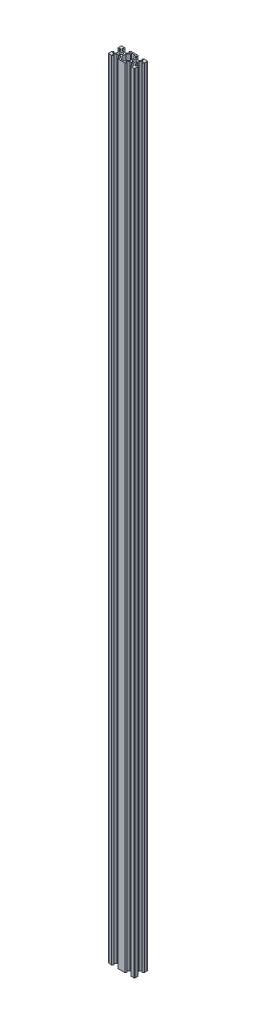
SolidWorks part; units mm, degrees
material "6063-T5"
material "6063-T5"
ref_plane "Plano frontal" through (0, 0, 0) normal (0, 0, 1) x (1, 0, 0)
ref_plane "Plano superior" through (0, 0, 0) normal (0, 1, 0) x (1, 0, 0)
ref_plane "Plano direito" through (0, 0, 0) normal (1, 0, 0) x (0, 0, -1)
sketch "Esboço1" plane through (0, 0, 0) normal (0, 0, 1) x (1, 0, 0)
  line L0 (0, 0) -> (0, 1200)
  dimension "D1" = 1200
other "Retangular PF20-12 - PERFIL 2040 V-SLOT(1)"
ref_plane "Plano1" through (0, 0, 0) normal (0, 1, 0) x (-1, 0, 0)
sketch "Sketch13" plane through (0, 0, 0) normal (0, 1, 0) x (-1, 0, 0)
  line L0 (-14.8, 10) -> (-13, 8.2)
  line L1 (-13, 8.2) -> (-15.5, 8.2)
  line L2 (-15.5, 8.2) -> (-15.5, 6.5607)
  line L3 (-15.5, 6.5607) -> (-12.9393, 4)
  line L4 (-12.9393, 4) -> (-10.3, 4)
  line L5 (-4.5, 6.5607) -> (-7.0607, 4)
  line L6 (-4.5, 8.2) -> (-4.5, 6.5607)
  line L7 (-7, 8.2) -> (-4.5, 8.2)
  line L8 (-5.2, 10) -> (-7, 8.2)
  line L9 (-10.3, 4) -> (-10, 3.7)
  line L10 (-9.7, 4) -> (-10, 3.7)
  line L11 (-9.7, 4) -> (-7.0607, 4)
  line L12 (-2.7, 8.2) -> (-2.7, 6.2393)
  line L13 (-2.7, 6.2393) -> (-6, 2.9393)
  line L14 (-2.7, 8.2) -> (2.7, 8.2)
  line L15 (2.7, 6.2393) -> (6, 2.9393)
  line L16 (2.7, 8.2) -> (2.7, 6.2393)
  line L17 (-5.2, -10) -> (5.2, -10)
  line L18 (-5.2, -10) -> (-7, -8.2)
  line L19 (-7, -8.2) -> (-4.5, -8.2)
  line L20 (-4.5, -8.2) -> (-4.5, -6.5607)
  line L21 (-4.5, -6.5607) -> (-7.0607, -4)
  line L22 (-7.0607, -4) -> (-9.7, -4)
  line L23 (-9.7, -4) -> (-10, -3.7)
  line L24 (-10.3, -4) -> (-10, -3.7)
  line L25 (-10.3, -4) -> (-12.9393, -4)
  line L26 (-15.5, -6.5607) -> (-12.9393, -4)
  line L27 (-15.5, -8.2) -> (-15.5, -6.5607)
  line L28 (-13, -8.2) -> (-15.5, -8.2)
  line L29 (-14.8, -10) -> (-13, -8.2)
  line L30 (-20, -4.8) -> (-20, -9)
  line L31 (-20, -4.8) -> (-18.2, -3)
  line L32 (-18.2, -3) -> (-18.2, -5.5)
  line L33 (-18.2, -5.5) -> (-16.5607, -5.5)
  line L34 (-16.5607, -5.5) -> (-14, -2.9393)
  line L35 (-14, -2.9393) -> (-14, -0.3)
  line L36 (-14, -0.3) -> (-13.7, 0)
  line L37 (-14, 0.3) -> (-13.7, 0)
  line L38 (-14, 0.3) -> (-14, 2.9393)
  line L39 (-16.5607, 5.5) -> (-14, 2.9393)
  line L40 (-18.2, 5.5) -> (-16.5607, 5.5)
  line L41 (-18.2, 3) -> (-18.2, 5.5)
  line L42 (-20, 4.8) -> (-18.2, 3)
  line L43 (-14.8, 10) -> (-19, 10)
  line L56 (5.2, 10) -> (-5.2, 10)
  line L57 (5.2, 10) -> (7, 8.2)
  line L58 (7, 8.2) -> (4.5, 8.2)
  line L59 (4.5, 8.2) -> (4.5, 6.5607)
  line L60 (4.5, 6.5607) -> (7.0607, 4)
  line L61 (9.7, 4) -> (7.0607, 4)
  line L62 (9.7, 4) -> (10, 3.7)
  line L63 (10.3, 4) -> (10, 3.7)
  line L64 (12.9393, 4) -> (10.3, 4)
  line L65 (15.5, 6.5607) -> (12.9393, 4)
  line L66 (15.5, 8.2) -> (15.5, 6.5607)
  line L67 (13, 8.2) -> (15.5, 8.2)
  line L68 (14.8, 10) -> (13, 8.2)
  line L69 (20, 4.8) -> (18.2, 3)
  line L70 (18.2, 3) -> (18.2, 5.5)
  line L71 (18.2, 5.5) -> (16.5607, 5.5)
  line L72 (16.5607, 5.5) -> (14, 2.9393)
  line L73 (14, 0.3) -> (14, 2.9393)
  line L74 (14, 0.3) -> (13.7, 0)
  line L75 (14, -0.3) -> (13.7, 0)
  line L76 (14, -2.9393) -> (14, -0.3)
  line L77 (16.5607, -5.5) -> (14, -2.9393)
  line L78 (18.2, -5.5) -> (16.5607, -5.5)
  line L79 (18.2, -3) -> (18.2, -5.5)
  line L80 (20, -4.8) -> (18.2, -3)
  line L81 (20, -9) -> (20, -4.8)
  line L82 (14.8, -10) -> (13, -8.2)
  line L83 (13, -8.2) -> (15.5, -8.2)
  line L84 (15.5, -8.2) -> (15.5, -6.5607)
  line L85 (15.5, -6.5607) -> (12.9393, -4)
  line L86 (10.3, -4) -> (12.9393, -4)
  line L87 (10.3, -4) -> (10, -3.7)
  line L88 (9.7, -4) -> (10, -3.7)
  line L89 (7.0607, -4) -> (9.7, -4)
  line L90 (4.5, -6.5607) -> (7.0607, -4)
  line L91 (4.5, -8.2) -> (4.5, -6.5607)
  line L92 (7, -8.2) -> (4.5, -8.2)
  line L93 (5.2, -10) -> (7, -8.2)
  line L99 (-6, 2.9393) -> (-6, -2.9393)
  line L100 (-2.7, -6.2393) -> (-6, -2.9393)
  line L101 (-2.7, -8.2) -> (-2.7, -6.2393)
  line L102 (-2.7, -8.2) -> (2.7, -8.2)
  line L103 (2.7, -8.2) -> (2.7, -6.2393)
  line L104 (2.7, -6.2393) -> (6, -2.9393)
  line L105 (6, 2.9393) -> (6, -2.9393)
  line L106 (-20, 9) -> (-20, 4.8)
  line L107 (-19, -10) -> (-14.8, -10)
  line L108 (19, 10) -> (14.8, 10)
  line L109 (20, 4.8) -> (20, 9)
  line L110 (14.8, -10) -> (19, -10)
  arc A3 (-20, -9) -> (-19, -10) centre (-19, -9) ccw
  arc A4 (-19, 10) -> (-20, 9) centre (-19, 9) ccw
  arc A5 (20, 9) -> (19, 10) centre (19, 9) ccw
  arc A6 (19, -10) -> (20, -9) centre (19, -9) ccw
  circle A7 centre (-10, 0) radius 2.5
  circle A8 centre (10, 0) radius 2.5
  point P1 (-20, 10)
  point P2 (20, 10)
  point P4 (20, 0)
  point P108 (0, 10)
  point P109 (0, 0)
  point P111 (20, -10)
  point P112 (10, -10)
  point P113 (-10, -10)
  point P114 (-20, -10)
  point P115 (-20, 0)
  point P116 (-10, 10)
  point P117 (10, 10)
  point P118 (-10, 0)
  point P119 (10, 0)
  point P120 (0, -10)
  point P121 (0, 0)
